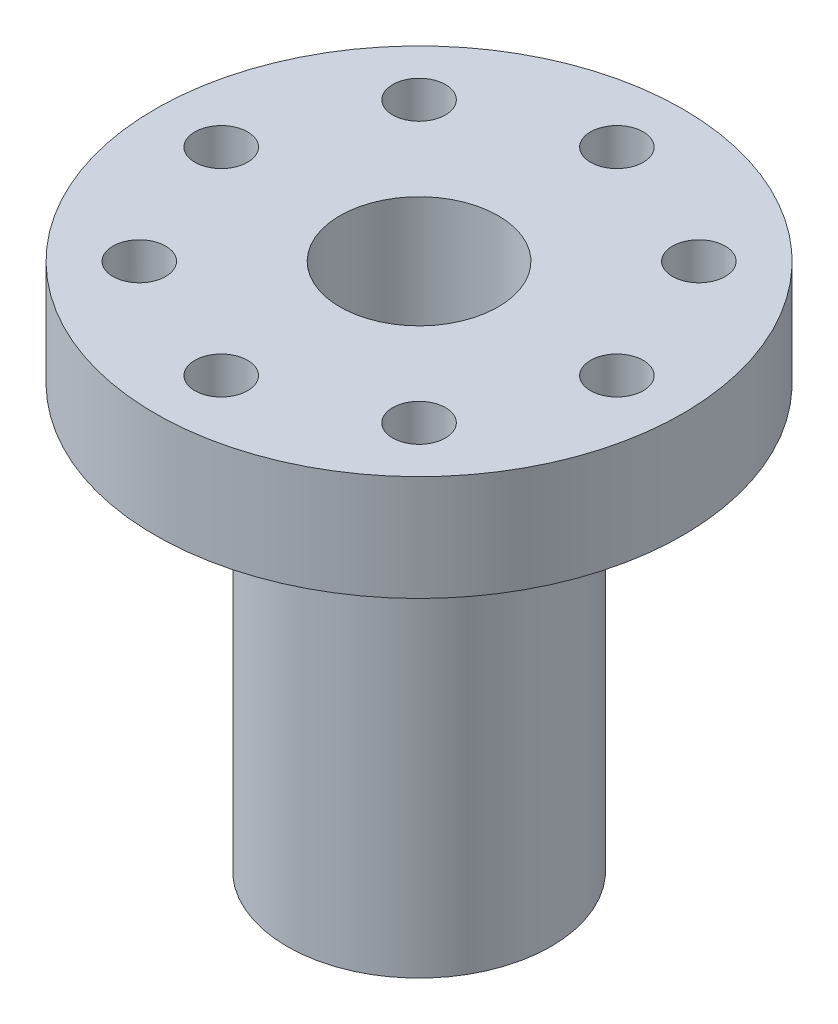
SolidWorks part; units mm, degrees
ref_plane "Front Plane" through (0, 0, 0) normal (0, 0, 1) x (1, 0, 0)
ref_plane "Top Plane" through (0, 0, 0) normal (0, 1, 0) x (1, 0, 0)
ref_plane "Right Plane" through (0, 0, 0) normal (1, 0, 0) x (0, 0, -1)
sketch "Sketch1" plane through (0, 0, 0) normal (0, 0, 1) x (1, 0, 0)
  line L0 (3.81, 25.4) -> (3.81, 4.572)
  line L1 (3.81, 4.572) -> (0.635, 4.572)
  line L2 (0.635, 4.572) -> (0.635, 0)
  line L3 (0.635, 0) -> (6.35, 0)
  line L4 (6.35, 0) -> (6.35, 20.32)
  line L5 (6.35, 20.32) -> (12.7, 20.32)
  line L6 (12.7, 20.32) -> (12.7, 25.4)
  line L7 (12.7, 25.4) -> (3.81, 25.4)
  line L8 (0, 0) -> (0, 14.386) construction
  dimension "D1" = 3.81
  dimension "D2" = 12.7
  dimension "D3" = 6.35
  dimension "D4" = 5.08
  dimension "D5" = 25.4
  dimension "D6" = 20.828
  dimension "D7" = 1.27
revolve "Revolve1" add sketch "Sketch1" angle 360 about L8
sketch "Sketch2" plane through (0, 0, 0) normal (0, -1, 0) x (1, 0, 0)
  circle A0 centre (0, 0) radius 2.54
  dimension "D1" = 5.08
extrude "Cut-Extrude1" cut sketch "Sketch2" against normal blind 3.5052
sketch "Sketch4" plane through (0, 25.4, 0) normal (0, 1, 0) x (1, 0, 0)
  line L0 (0, 9.525) -> (0, 0) construction
  circle A0 centre (0, 9.525) radius 1.27
  circle A1 centre (0, 0) radius 9.525 construction
  dimension "D1" = 19.05
  dimension "D2" = 2.54
extrude "Cut-Extrude2" cut sketch "Sketch4" against normal through all
pattern_circular "CirPattern1" count 8 over 360 about axis through (0, 0, 0) along (0, 1, 0) of "Cut-Extrude2"
